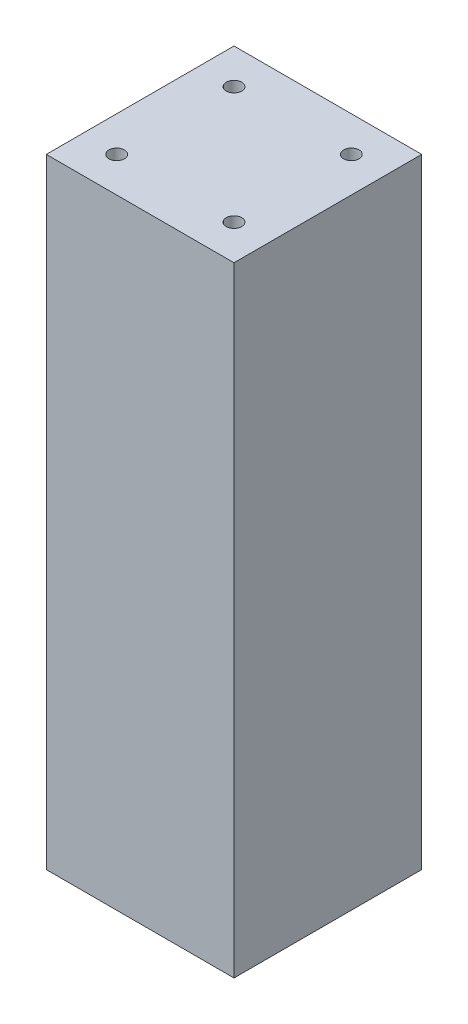
SolidWorks part; units mm, degrees
ref_plane "Front Plane" through (0, 0, 0) normal (0, 0, 1) x (1, 0, 0)
ref_plane "Top Plane" through (0, 0, 0) normal (0, 1, 0) x (1, 0, 0)
ref_plane "Right Plane" through (0, 0, 0) normal (1, 0, 0) x (0, 0, -1)
sketch "Skizze1" plane through (0, 0, 0) normal (0, 1, 0) x (1, 0, 0)
  line L1 (-20, 20) -> (20, 20)
  line L2 (-20, 20) -> (-20, -20)
  line L3 (-20, -20) -> (20, -20)
  line L4 (20, 20) -> (20, -20)
  line L5 (0, -20) -> (0, 20) construction
  line L6 (-20, 0) -> (20, 0) construction
  point P56 (0, 0)
  dimension "D1" = 40
  dimension "D2" = 40
extrude "Aufsatz-Linear austragen1" add sketch "Skizze1" along normal mid plane 132
hole_wizard "M4 Gewindebohrung1" positions "Skizze2" profile "Skizze3" tap size "M4" standard "DIN"
sketch "Skizze2" plane through (0, 66, 0) normal (0, 1, 0) x (1, 0, 0)
  line L0 (0, 20) -> (0, -20) construction
  line L1 (20, 20) -> (-20, 20) construction
  line L2 (-20, -20) -> (20, -20) construction
  line L5 (20, 0) -> (-20, 0) construction
  line L6 (20, -20) -> (20, 20) construction
  line L7 (-20, 20) -> (-20, -20) construction
  point P0 (-12.5, 12.5)
  point P24 (12.5, 12.5)
  point P25 (12.5, -12.5)
  point P26 (-12.5, -12.5)
  dimension "D1" = 25
  dimension "D2" = 25
sketch "Skizze3" plane through (-12.5, 66, -12.5) normal (1, 0, 0) x (0, 0, 1)
  line L0 (0, 0) -> (0, 12.4914)
  line L1 (0, 12.4914) -> (1.65, 11.5)
  line L2 (1.65, 11.5) -> (1.65, 0)
  line L5 (1.65, 0) -> (0, 0)
  line L10 (0, 12.4914) -> (-1.65, 11.5) construction
  line L11 (0, -6.35) -> (0, 107.95) construction
  dimension "Bohrerdurchmesser" = 3.3
  dimension "Bohrungstiefe" = 11.5
  dimension "Spitzenwinkel" = 118
cosmetic thread "Bohrungsgewinde1"
cosmetic thread "Bohrungsgewinde2"
cosmetic thread "Bohrungsgewinde3"
cosmetic thread "Bohrungsgewinde4"
hole_wizard "M6 Gewindebohrung1" positions "Skizze8" profile "Skizze7" tap size "M6" standard "DIN"
sketch "Skizze8" plane through (0, -66, 0) normal (0, -1, 0) x (-1, 0, 0)
  line L0 (-20, 0) -> (20, 0) construction
  line L1 (-20, -20) -> (-20, 20) construction
  line L2 (20, 20) -> (20, -20) construction
  line L4 (0, 20) -> (0, -20) construction
  line L5 (-20, 20) -> (20, 20) construction
  line L6 (20, -20) -> (-20, -20) construction
  point P0 (10, 12.5)
  point P2 (10, -12.5)
  dimension "D1" = 25
  dimension "D2" = 10
cosmetic thread "Bohrungsgewinde6"
cosmetic thread "Bohrungsgewinde7"
sketch "Skizze7" plane through (-10, -66, -12.5) normal (1, 0, 0) x (0, 0, -1)
  line L0 (0, 0) -> (0, 18.5022)
  line L1 (0, 18.5022) -> (2.5, 17)
  line L2 (2.5, 17) -> (2.5, 0.525)
  line L3 (2.5, 0.525) -> (3.025, 0)
  line L5 (3.025, 0) -> (0, 0)
  line L6 (-2.5, 0.525) -> (-3.025, 0) construction
  line L10 (0, 18.5022) -> (-2.5, 17) construction
  line L11 (0, -6.35) -> (0, 107.95) construction
  dimension "Bohrerdurchmesser" = 5
  dimension "Bohrungstiefe" = 17
  dimension "Senkdurchmesser (Oben)" = 6.05
  dimension "Senkwinkel (Oben)" = 90
  dimension "Spitzenwinkel" = 118
hole_wizard "Ø6.0mm Stiftloch1" positions "Skizze9" profile "Skizze10" hole size "Ø6.0" standard "DIN"
sketch "Skizze9" plane through (0, -66, 0) normal (0, -1, 0) x (-1, 0, 0)
  line L0 (20, 0) -> (-20, 0) construction
  line L1 (20, 20) -> (20, -20) construction
  line L2 (-20, -20) -> (-20, 20) construction
  line L4 (0, 20) -> (0, -20) construction
  line L5 (-20, 20) -> (20, 20) construction
  line L6 (20, -20) -> (-20, -20) construction
  point P0 (10, 0)
  point P2 (-10, 0)
  dimension "D1" = 20
sketch "Skizze10" plane through (-10, -66, 0) normal (1, 0, 0) x (0, 0, -1)
  line L0 (0, 0) -> (0, 18.8026)
  line L1 (0, 18.8026) -> (3, 17)
  line L2 (3, 17) -> (3, 0)
  line L5 (3, 0) -> (0, 0)
  line L10 (0, 18.8026) -> (-3, 17) construction
  line L11 (0, -6.35) -> (0, 107.95) construction
  dimension "Bohrerdurchmesser" = 6
  dimension "Bohrungstiefe" = 17
  dimension "Spitzenwinkel" = 118
